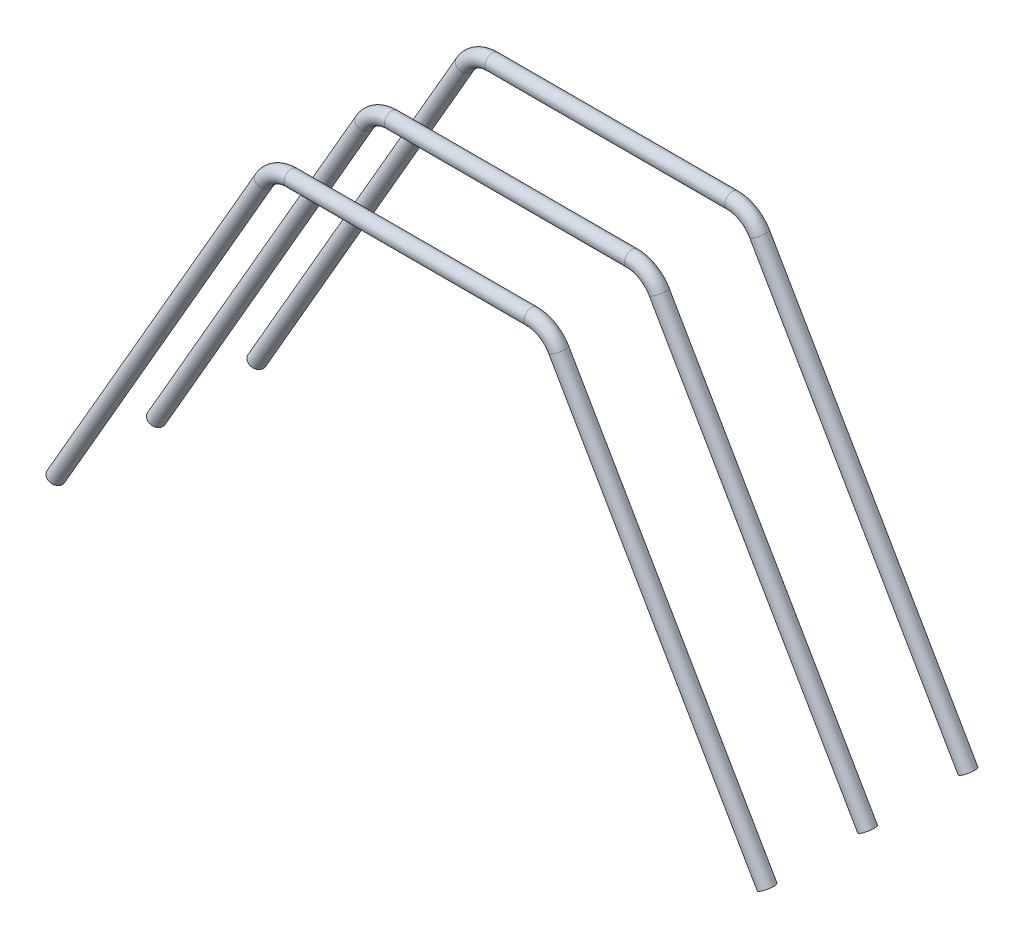
SolidWorks part; units mm, degrees
material "AISI 1020"
ref_plane "Спереди" through (0, 0, 0) normal (0, 0, 1) x (1, 0, 0)
ref_plane "Сверху" through (0, 0, 0) normal (0, 1, 0) x (1, 0, 0)
ref_plane "Справа" through (0, 0, 0) normal (1, 0, 0) x (0, 0, -1)
sketch "Эскиз2" plane through (0, 0, 0) normal (1, 0, 0) x (0, 0, -1)
  line L0 (-150, -16) -> (150, -16) construction
  circle A0 centre (0, -22) radius 6
  dimension "D1" = 12
sketch "Эскиз3" plane through (0, 0, 0) normal (0, 0, 1) x (1, 0, 0)
  line L0 (0, -22) -> (95.5662, -22)
  line L1 (117.2169, -34.5) -> (283.2051, -322)
  arc A0 (95.5662, -22) -> (117.2169, -34.5) centre (95.5662, -47) cw
  point P8 (110, -22)
  dimension "D3" = 25
  dimension "D1" = 60
  dimension "D2" = 300
sweep "По траектории1" add profiles "Эскиз2" path "Эскиз3"
mirror "Зеркальное отражение1" about plane through (0, -22, 0) normal (1, 0, 0) of "По траектории1"
pattern_linear "Линейный массив1" count 2 spacing 80 along (0, 0, -1) of bodies 104
mirror "Зеркальное отражение2" about plane through (0, 0, 0) normal (0, 0, 1) of bodies 105
